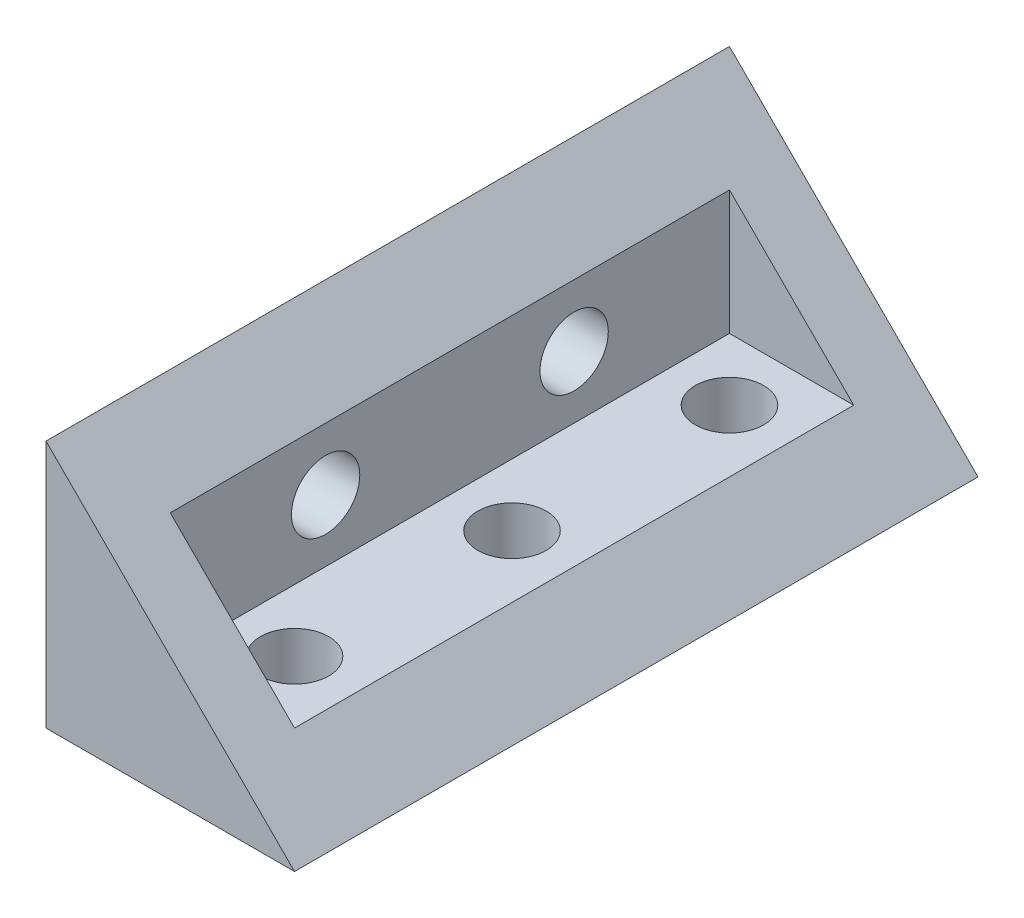
SolidWorks part; units mm, degrees
ref_plane "Plan de face" through (0, 0, 0) normal (0, 0, 1) x (1, 0, 0)
ref_plane "Plan de dessus" through (0, 0, 0) normal (0, 1, 0) x (1, 0, 0)
ref_plane "Plan de droite" through (0, 0, 0) normal (1, 0, 0) x (0, 0, -1)
sketch "Esquisse1" plane through (0, 0, 0) normal (0, 0, 1) x (1, 0, 0)
  line L0 (-13.6945, 7.95) -> (6.3055, -12.05)
  line L2 (-13.6945, 7.95) -> (-13.6945, -12.05)
  line L3 (-13.6945, -12.05) -> (6.3055, -12.05)
  dimension "D1" = 20
extrude "Boss.-Extru.1" add sketch "Esquisse1" along normal blind 5
sketch "Esquisse2" plane through (0, 0, 5) normal (0, 0, 1) x (1, 0, 0)
  line L0 (-13.6945, -12.05) -> (6.3055, -12.05)
  line L1 (6.3055, -12.05) -> (-13.6945, 7.95) construction
  line L2 (-13.6945, -12.05) -> (6.3055, -12.05) construction
  line L3 (6.3055, -12.05) -> (1.3055, -7.05)
  line L4 (1.3055, -7.05) -> (-8.6945, -7.05)
  line L5 (-8.6945, -7.05) -> (-8.6945, 2.95)
  line L6 (-8.6945, 2.95) -> (-13.6945, 7.95)
  line L7 (-13.6945, 7.95) -> (-13.6945, -12.05) construction
  line L8 (-13.6945, 7.95) -> (-13.6945, -12.05)
  dimension "D1" = 5
extrude "Boss.-Extru.2" add sketch "Esquisse2" along normal blind 45
sketch "Esquisse3" plane through (0, 0, 50) normal (0, 0, 1) x (1, 0, 0)
  line L0 (-13.6945, 7.95) -> (6.3055, -12.05)
  line L1 (6.3055, -12.05) -> (-13.6945, -12.05)
  line L2 (-13.6945, -12.05) -> (-13.6945, 7.95)
extrude "Boss.-Extru.3" add sketch "Esquisse3" along normal blind 5
sketch "Esquisse4" plane through (-8.6945, 0, 0) normal (1, 0, 0) x (0, 0, -1)
  line L0 (-55, -12.05) -> (0, -12.05) construction
  line L2 (-37.5, -2.05) -> (-17.5, -2.05) construction
  line L3 (-50, 2.95) -> (-5, 2.95) construction
  circle A0 centre (-17.5, -2.05) radius 2.75
  circle A1 centre (-37.5, -2.05) radius 2.75
  point P4 (-27.5, -2.05)
  point P7 (-27.5, 2.95)
  dimension "D1" = 5.5
  dimension "D2" = 10
  dimension "D3" = 20
extrude "Enlèv. mat.-Extru.1" cut sketch "Esquisse4" against normal up to next
sketch "Esquisse5" plane through (0, -7.05, 0) normal (0, 1, 0) x (1, 0, 0)
  line L0 (-13.6945, -55) -> (-13.6945, 0) construction
  line L1 (1.3055, -50) -> (-8.6945, -50) construction
  line L2 (1.3055, -5) -> (-8.6945, -5) construction
  line L3 (-3.6945, -45) -> (-3.6945, -10) construction
  circle A0 centre (-3.6945, -45) radius 2.75
  circle A1 centre (-3.6945, -27.5) radius 2.75
  circle A2 centre (-3.6945, -10) radius 2.75
  point P12 (0, 0)
  point P13 (-3.6945, -27.5)
  point P14 (0, 0)
  dimension "D2" = 5.5
  dimension "D1" = 10
  dimension "D3" = 5
  dimension "D4" = 5
extrude "Enlèv. mat.-Extru.2" cut sketch "Esquisse5" against normal up to next
